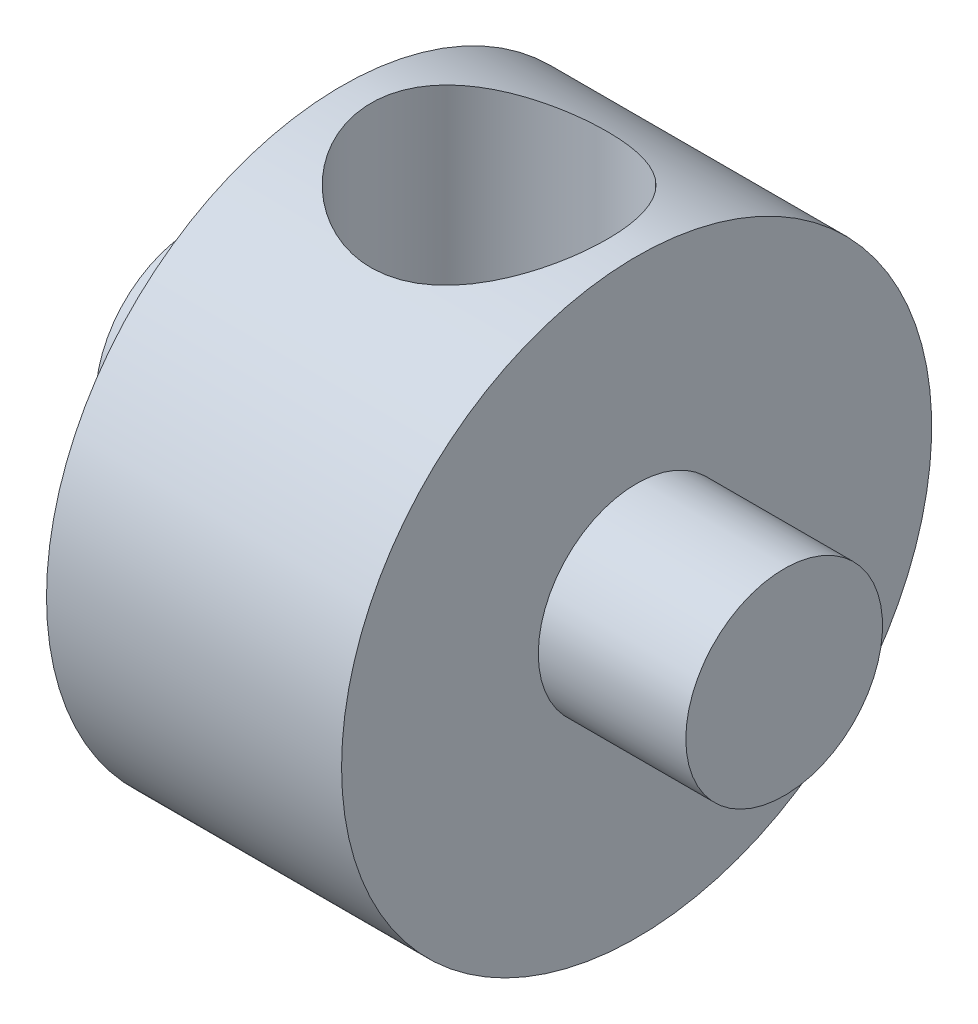
SolidWorks part; units mm, degrees
ref_plane "Front Plane" through (0, 0, 0) normal (0, 0, 1) x (1, 0, 0)
ref_plane "Top Plane" through (0, 0, 0) normal (0, 1, 0) x (1, 0, 0)
ref_plane "Right Plane" through (0, 0, 0) normal (1, 0, 0) x (0, 0, -1)
sketch "Sketch1" plane through (0, 0, 0) normal (0, 0, 1) x (1, 0, 0)
  line L0 (0, 0) -> (0, 9.525)
  line L1 (-4.7625, 0) -> (4.7625, 0)
  line L2 (-4.7625, 9.525) -> (4.7625, 9.525)
  line L3 (4.7625, 0) -> (4.7625, 9.525)
  line L4 (4.7625, 0) -> (4.7625, 3.175)
  line L5 (4.7625, 0) -> (9.525, 0)
  line L6 (4.7625, 3.175) -> (9.525, 3.175)
  line L7 (9.525, 0) -> (9.525, 3.175)
  line L8 (-4.7625, 0) -> (-9.525, 0)
  line L9 (-9.525, 0) -> (-9.525, 3.175)
  line L10 (-4.7625, 3.175) -> (-9.525, 3.175)
  line L11 (-4.7625, 0) -> (-4.7625, 9.525)
  point P12 (0, 0)
  dimension "D1" = 4.7625
  dimension "D2" = 4.7625
  dimension "D3" = 9.525
  dimension "D4" = 3.175
revolve "Revolve1" add sketch "Sketch1" angle 360 about L1
sketch "Sketch2" plane through (0, 0, 0) normal (0, 1, 0) x (1, 0, 0)
  circle A0 centre (0, 0) radius 3.81
  dimension "D1" = 7.62
extrude "Cut-Extrude1" cut sketch "Sketch2" against normal through all both and the other way through all
